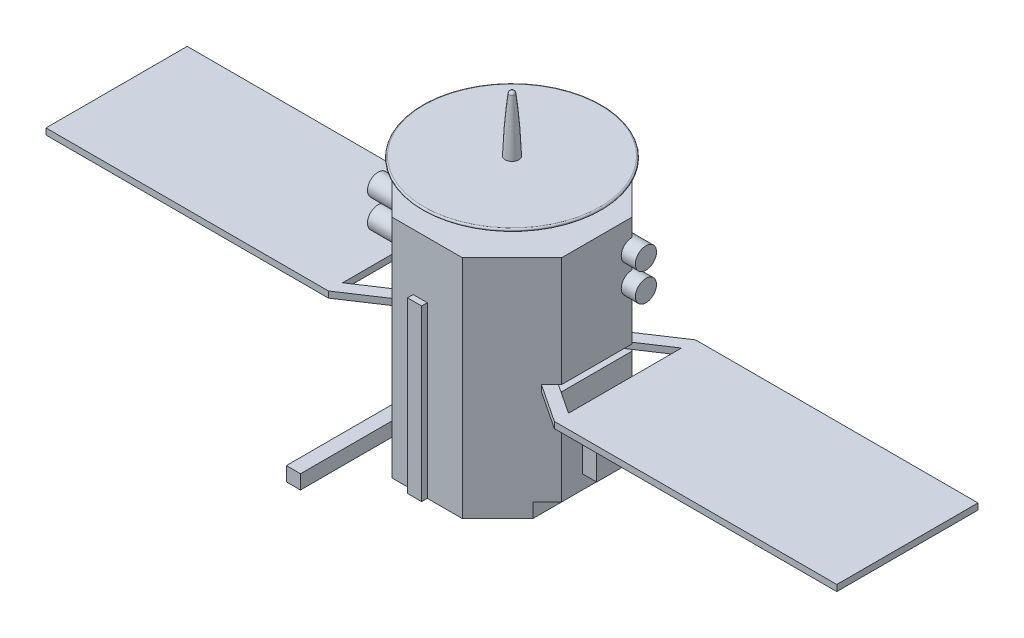
SolidWorks part; units mm, degrees
ref_plane "Front Plane" through (0, 0, 0) normal (0, 0, 1) x (1, 0, 0)
ref_plane "Top Plane" through (0, 0, 0) normal (0, 1, 0) x (1, 0, 0)
ref_plane "Right Plane" through (0, 0, 0) normal (1, 0, 0) x (0, 0, -1)
sketch "Sketch1" plane through (0, 0, 0) normal (0, 1, 0) x (1, 0, 0)
  line L0 (12.4264, -30) -> (30, -12.4264)
  line L1 (30, 12.4264) -> (12.4264, 30)
  line L2 (12.4264, 30) -> (-12.4264, 30)
  line L3 (-12.4264, 30) -> (-30, 12.4264)
  line L4 (-30, 12.4264) -> (-30, -12.4264)
  line L5 (-30, -12.4264) -> (-12.4264, -30)
  line L6 (-12.4264, -30) -> (12.4264, -30)
  line L7 (30, -12.4264) -> (30, 12.4264)
  circle A0 centre (0, 0) radius 30 construction
  dimension "D1" = 60
extrude "Boss-Extrude1" add sketch "Sketch1" along normal blind 80
ref_plane "Plane1" through (0, 40, 0) normal (0, 1, 0) x (1, 0, 0)
sketch "Sketch3" plane through (0, 40, 0) normal (0, 1, 0) x (1, 0, 0)
  line L0 (40, 25) -> (10, 5.1)
  line L1 (10, 5.1) -> (10, -5.1)
  line L2 (10, -5.1) -> (40, -25)
  line L3 (40, 25) -> (40, -25)
  point P2 (10, 0)
  dimension "D1" = 10.2
  dimension "D2" = 30
  dimension "D3" = 10
  dimension "D4" = 50
extrude "Cut-Extrude1" cut sketch "Sketch3" against normal blind 1.1 and the other way blind 1.1
mirror "Mirror1" about plane through (0, 0, 0) normal (1, 0, 0) of "Cut-Extrude1"
sketch "Sketch4" plane through (0, 80, 0) normal (0, 1, 0) x (1, 0, 0)
  line L0 (12.4264, 30) -> (-12.4264, 30) construction
  line L1 (0, 30) -> (30, 30)
  line L2 (0, 30) -> (0, -30)
  line L3 (0, -30) -> (30, -30)
  line L4 (30, 30) -> (30, -30)
  line L5 (-12.4264, -30) -> (12.4264, -30) construction
  line L6 (30, -12.4264) -> (30, 12.4264) construction
extrude "Cut-Extrude2" [suppressed] cut sketch "Sketch4" against normal through all
sketch "Sketch5" plane through (0, 80, 0) normal (0, 1, 0) x (1, 0, 0)
  line L1 (30, -12.4264) -> (30, 12.4264) construction
  line L3 (12.4264, 30) -> (-12.4264, 30) construction
  circle A0 centre (0, 0) radius 5.1
  point P4 (30, 0)
  point P7 (0, 30)
  dimension "D1" = 10.2
extrude "Cut-Extrude3" cut sketch "Sketch5" against normal blind 12
sketch "Sketch6" plane through (-30, 0, 0) normal (-1, 0, 0) x (0, 0, 1)
  line L0 (12.4264, 80) -> (12.4264, 41.1) construction
  line L1 (-12.4264, 0) -> (12.4264, 0) construction
  line L2 (-5, 20) -> (5, 20)
  line L3 (-5, 20) -> (-5, 10)
  line L4 (-5, 10) -> (5, 10)
  line L5 (5, 20) -> (5, 10)
  line L6 (-12.4264, 80) -> (12.4264, 80) construction
  circle A0 centre (12.4264, 70) radius 3.75
  circle A1 centre (12.4264, 60) radius 3.75
  point P10 (0, 10)
  dimension "D5" = 7.5
  dimension "D1" = 10
  dimension "D2" = 10
  dimension "D3" = 10
  dimension "D4" = 10
extrude "Boss-Extrude2" add sketch "Sketch6" along normal blind 5 and the other way blind 12
sketch "Sketch7" plane through (0, 0, 30) normal (0, 0, 1) x (1, 0, 0)
  line L1 (0, 0) -> (-5, 0)
  line L2 (0, 0) -> (0, 60)
  line L3 (0, 60) -> (-5, 60)
  line L4 (-5, 0) -> (-5, 60)
  line L5 (-12.4264, 0) -> (12.4264, 0) construction
  line L6 (-12.4264, 80) -> (-12.4264, 0) construction
  point P4 (0, 0)
  point P5 (0, 0)
  dimension "D1" = 7.4264
  dimension "D2" = 60
extrude "Boss-Extrude3" add sketch "Sketch7" along normal blind 2
sketch "Sketch8" plane through (0, 0, 30) normal (0, 0, 1) x (1, 0, 0)
  line L1 (-30, 0) -> (-24.9, 0)
  line L2 (-30, 0) -> (-30, 5.1)
  line L3 (-30, 5.1) -> (-24.9, 5.1)
  line L4 (-24.9, 0) -> (-24.9, 5.1)
  dimension "D1" = 5.1
extrude "Cut-Extrude4" cut sketch "Sketch8" against normal through all
sketch "Sketch9" plane through (0, 38.9, 0) normal (0, 1, 0) x (1, 0, 0)
  line L0 (-10, -5.1) -> (-10, 5.1)
  line L1 (-10, 5.1) -> (-40, 25)
  line L2 (-10, -5.1) -> (-40, -25)
  line L3 (-40, 25) -> (-140, 25)
  line L4 (-140, 25) -> (-140, -25)
  line L5 (-140, -25) -> (-40, -25)
  line L6 (-10, -5.1) -> (-26.4287, -15.9977) construction
  line L7 (-26.4287, 15.9977) -> (-10, 5.1) construction
  line L15 (-40, 20) -> (-40, -20)
  line L16 (-40, -20) -> (-15, -3.4167)
  line L17 (-15, -3.4167) -> (-15, 3.4167)
  line L18 (-15, 3.4167) -> (-40, 20)
  line L19 (0, -34.1) -> (0, 34.1) construction
  line L20 (15, 3.4167) -> (40, 20)
  line L21 (15, -3.4167) -> (15, 3.4167)
  line L22 (40, -20) -> (15, -3.4167)
  line L23 (40, 20) -> (40, -20)
  line L24 (140, -25) -> (40, -25)
  line L25 (140, 25) -> (140, -25)
  line L26 (40, 25) -> (140, 25)
  line L27 (10, -5.1) -> (40, -25)
  line L28 (10, 5.1) -> (40, 25)
  line L29 (10, -5.1) -> (10, 5.1)
  point P12 (-19.1251, -2.6106)
  point P25 (-15, 0)
  point P26 (-10, 0)
  point P27 (-40, 20.5659)
  point P28 (-15, 2.3533)
  point P29 (-40, 20)
  point P30 (-40, 20)
  point P31 (0, 0)
  point P32 (-15, -3.1428)
  dimension "D1" = 50
  dimension "D2" = 100
  dimension "D3" = 40
  dimension "D4" = 5
extrude "Boss-Extrude4" add sketch "Sketch9" along normal up to surface (2.2 mm away) up to face at (-22.1429, 41.1, 0)
pattern_circular "CirPattern1" count 2 over 360 about axis through (0, 0, 0) along (0, 1, 0) of "Boss-Extrude2", "Boss-Extrude3", "Cut-Extrude4"
sketch "Sketch10" plane through (0, 0, 0) normal (0, 0, 1) x (1, 0, 0)
  line L0 (32.7231, 90) -> (2.3931, 90)
  line L1 (0, 68) -> (0, 110.12)
  line L2 (5.1, 68) -> (-5.1, 68) construction
  line L3 (0, 70) -> (2.5, 70) construction
  line L7 (0, 68) -> (5.1, 68)
  line L8 (5.1, 68) -> (5.1, 80)
  line L9 (2.5, 70) -> (2.5, 83) construction
  arc A0 (5.1, 80) -> (32.7231, 90) centre (2.6427, 129.9396) ccw
  arc A1 (0.9934, 109.2345) -> (0, 110.12) centre (0, 109.12) ccw
  arc A4 (2.5, 83) -> (0.9934, 109.2345) centre (-226.6681, 83) ccw construction
  arc A6 (2.3931, 90) -> (0.9934, 109.2345) centre (-226.6681, 83) ccw
  point P7 (0, 0)
  point P13 (3.1401, 70)
  point P18 (7.0645, 90)
  point P19 (30.9179, 90)
  point P20 (2.6262, 70)
  point P22 (30.4994, 90)
  point P23 (5.1, 80)
  point P24 (34.8516, 90)
  point P25 (4.6322, 90)
  point P26 (34.3565, 90)
  point P27 (34.3565, 90)
  point P28 (0.9383, 109.3458)
  point P29 (0, 0)
  point P30 (0, 120.5662)
  dimension "D1" = 50
  dimension "D5" = 1
  dimension "D6" = 10
  dimension "D8" = 2.5
  dimension "D2" = 10
  dimension "D3" = 19.12
  dimension "D4" = 13
  dimension "D7" = 30.33
revolve "Revolve2" add sketch "Sketch10" angle 360 about L1
fillet "Fillet1" radius 0.5 1 edges at (0, 90, -32.7231)
sketch "Sketch11" plane through (0, 0, 0) normal (0, 0, 1) x (1, 0, 0)
  line L1 (-24.9, 5.1) -> (-29.9, 5.1)
  line L2 (-24.9, 5.1) -> (-24.9, 0.1)
  line L3 (-24.9, 0.1) -> (-29.9, 0.1)
  line L4 (-29.9, 5.1) -> (-29.9, 0.1)
  dimension "D1" = 5
extrude "Boss-Extrude5" add sketch "Sketch11" along normal blind 50 and the other way blind 50
